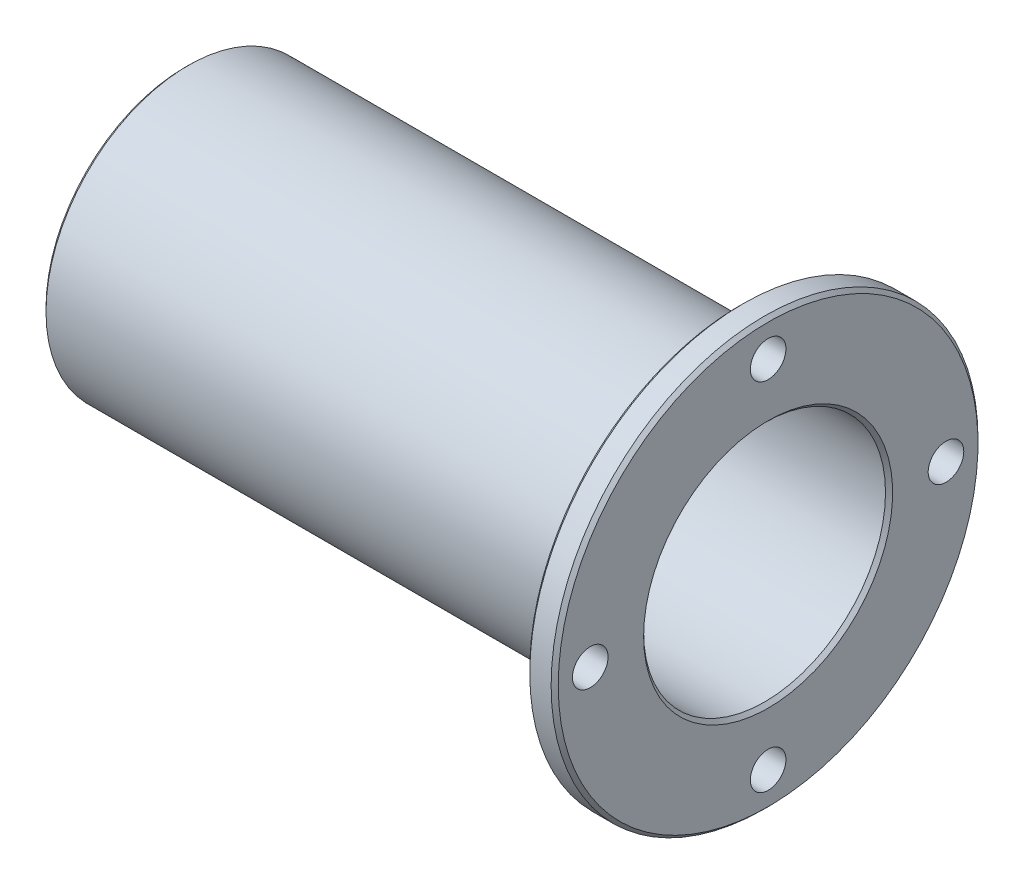
SolidWorks part; units mm, degrees
material "Alliage 1060"
ref_plane "Face" through (0, 0, 0) normal (0, 0, 1) x (1, 0, 0)
ref_plane "Dessus" through (0, 0, 0) normal (0, 1, 0) x (1, 0, 0)
ref_plane "Droite" through (0, 0, 0) normal (1, 0, 0) x (0, 0, -1)
sketch "Esquisse1" plane through (0, 0, 0) normal (0, 0, 1) x (1, 0, 0)
  line L0 (0, 0) -> (54.7909, 0) construction
  line L1 (0, 10) -> (0, 20)
  line L2 (0, 20) -> (78, 20)
  line L3 (78, 20) -> (78, 30)
  line L4 (78, 30) -> (82, 30)
  line L5 (0, 10) -> (4, 10)
  line L6 (4, 10) -> (4, 17)
  line L7 (4, 17) -> (82, 17)
  line L8 (82, 30) -> (82, 17)
  dimension "D1" = 34
  dimension "D2" = 20
  dimension "D3" = 4
  dimension "D4" = 40
  dimension "D5" = 78
  dimension "D6" = 60
  dimension "D7" = 4
revolve "Révolution1" add sketch "Esquisse1" angle 360 about L0
chamfer "Chanfrein1" distance 0.5 angle 45 5 edges at (78, 0, 30) (82, 0, 30) (82, 0, 17) (4, 0, 10) (0, 0, 20)
sketch "Esquisse2" plane through (0, 0, 0) normal (-1, 0, 0) x (0, 0, 1)
  line L0 (-13, 0) -> (13, 0) construction
  line L1 (0, 13) -> (0, -13) construction
  circle A0 centre (0, 0) radius 13 construction
  dimension "D1" = 26
hole_wizard "Fraisage pour vis à tête fraisée M31" positions "Esquisse4" profile "Esquisse3" countersink size "M3" standard "Din" end condition through all
sketch "Esquisse4" plane through (0, 0, 0) normal (-1, 0, 0) x (0, 0, 1)
  point P0 (0, 13)
  point P3 (13, 0)
  point P6 (0, -13)
  point P9 (-13, 0)
sketch "Esquisse3" plane through (0, 13, 0) normal (0, 1, 0) x (0, 0, 1)
  line L0 (0, 0) -> (0, 82)
  line L1 (0, 82) -> (1.6, 82)
  line L2 (1.6, 82) -> (1.6, 2.05)
  line L3 (1.6, 2.05) -> (3.65, 0)
  line L5 (3.65, 0) -> (0, 0)
  line L6 (-1.6, 2.05) -> (-3.65, 0) construction
  line L11 (0, -6.35) -> (0, 107.95) construction
  dimension "Diamètre du perçage jusqu'au prochain" = 3.2
  dimension "Profondeur du perçage jusqu'au prochain" = 82
  dimension "Diamètre du fraisage entrant" = 7.3
  dimension "Angle du fraisage entrant" = 90
sketch "Esquisse5" plane through (82, 0, 0) normal (1, 0, 0) x (0, 0, -1)
  line L0 (0, -25) -> (0, 25) construction
  line L2 (-25, 0) -> (25, 0) construction
  circle A0 centre (0, 0) radius 25 construction
  circle A1 centre (0, 25) radius 2.5
  circle A2 centre (25, 0) radius 2.5
  circle A3 centre (-25, 0) radius 2.5
  circle A4 centre (0, -25) radius 2.5
  dimension "D1" = 50
extrude "Enlèv. mat.-Extru.1" cut sketch "Esquisse5" against normal up to next
